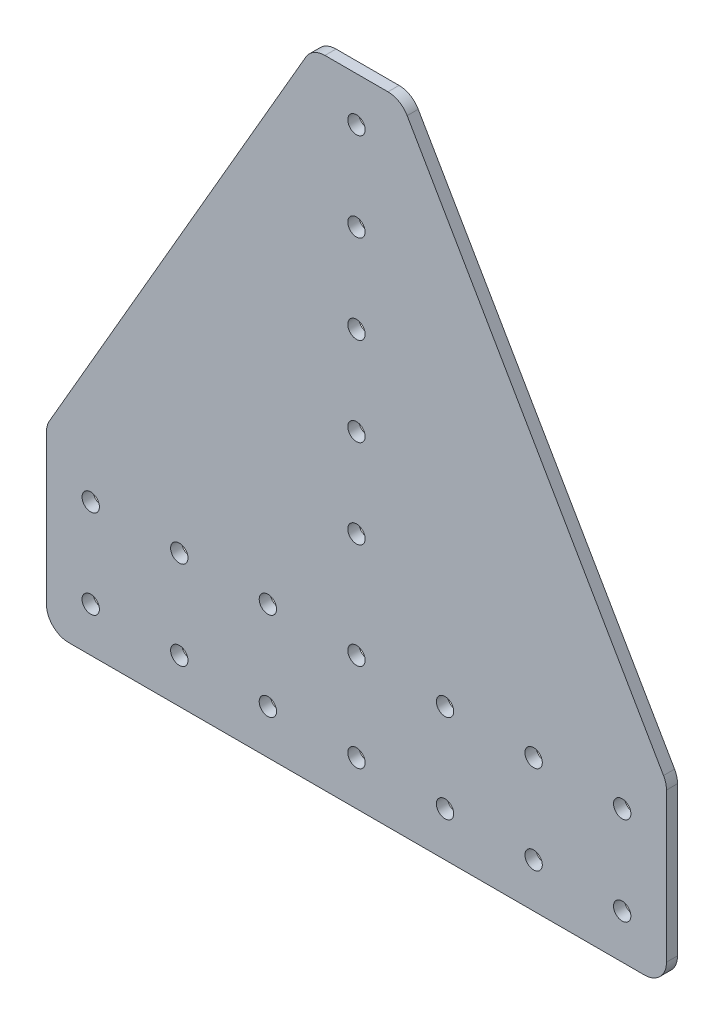
SolidWorks part; units mm, degrees
material "6061-T6 (SS)"
ref_plane "Front Plane" through (0, 0, 0) normal (0, 0, 1) x (1, 0, 0)
ref_plane "Top Plane" through (0, 0, 0) normal (0, 1, 0) x (1, 0, 0)
ref_plane "Right Plane" through (0, 0, 0) normal (1, 0, 0) x (0, 0, -1)
sketch "Sketch1" plane through (0, 0, 0) normal (0, 0, 1) x (1, 0, 0)
  line L0 (0, 0) -> (0, 50.8)
  line L1 (0, 50.8) -> (76.2, 182.5625)
  line L2 (76.2, 182.5625) -> (101.6, 182.5625)
  line L3 (101.6, 182.5625) -> (177.8, 50.8)
  line L4 (177.8, 50.8) -> (177.8, 0)
  line L5 (177.8, 0) -> (0, 0)
  dimension "D1" = 50.8
  dimension "D2" = 25.4
  dimension "D3" = 177.8
  dimension "D4" = 76.2
  dimension "D5" = 131.7625
extrude "Boss-Extrude1" add sketch "Sketch1" against normal blind 3.175 contours L1 L2 L3 L4 L5 L0
sketch "Sketch2" plane through (0, 0, 0) normal (0, 0, 1) x (1, 0, 0)
  line L0 (177.8, 0) -> (0, 0) construction
  line L1 (0, 0) -> (0, 50.8) construction
  line L2 (76.2, 182.5625) -> (101.6, 182.5625) construction
  circle A0 centre (12.7, 12.7) radius 2.4892
  circle A1 centre (38.1, 12.7) radius 2.4892
  circle A2 centre (63.5, 12.7) radius 2.4892
  circle A3 centre (88.9, 12.7) radius 2.4892
  circle A4 centre (114.3, 12.7) radius 2.4892
  circle A5 centre (139.7, 12.7) radius 2.4892
  circle A6 centre (165.1, 12.7) radius 2.4892
  circle A21 centre (38.1, 38.1) radius 2.4892
  circle A22 centre (63.5, 38.1) radius 2.4892
  circle A23 centre (88.9, 38.1) radius 2.4892
  circle A24 centre (114.3, 38.1) radius 2.4892
  circle A25 centre (139.7, 38.1) radius 2.4892
  circle A26 centre (165.1, 38.1) radius 2.4892
  circle A41 centre (12.7, 38.1) radius 2.4892
  circle A42 centre (88.9, 169.8625) radius 2.4892
  circle A43 centre (88.9, 144.4625) radius 2.4892
  circle A44 centre (88.9, 119.0625) radius 2.4892
  circle A45 centre (88.9, 93.6625) radius 2.4892
  circle A46 centre (88.9, 68.2625) radius 2.4892
  dimension "D1" = 4.9784
  dimension "D6" = 4.9784
  dimension "D2" = 12.7
  dimension "D3" = 12.7
  dimension "D7" = 12.7
  dimension "D8" = 12.7
  dimension "D4" = 7
  dimension "D5" = 2
  dimension "D9" = 5
extrude "Cut-Extrude1" cut sketch "Sketch2" against normal through all
fillet "Fillet1" radius 6.35 6 edges at (0, 0, -1.5875) (177.8, 0, -1.5875) (177.8, 50.8, -1.5875) (101.6, 182.5625, -1.5875) (0, 50.8, -1.5875) (76.2, 182.5625, -1.5875)
